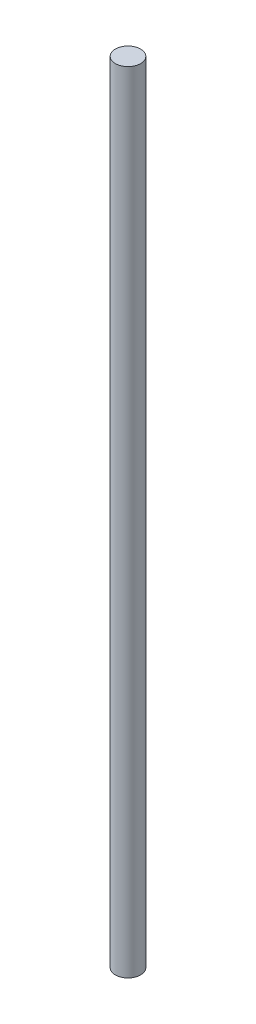
SolidWorks part; units mm, degrees
material "Chrome Stainless Steel"
ref_plane "Front Plane" through (0, 0, 0) normal (0, 0, 1) x (1, 0, 0)
ref_plane "Top Plane" through (0, 0, 0) normal (0, 1, 0) x (1, 0, 0)
ref_plane "Right Plane" through (0, 0, 0) normal (1, 0, 0) x (0, 0, -1)
sketch "Sketch1" plane through (0, 0, 0) normal (0, 1, 0) x (1, 0, 0)
  circle A0 centre (0, 0) radius 3.175
extrude "Boss-Extrude1" add sketch "Sketch1" along normal blind 198.57
